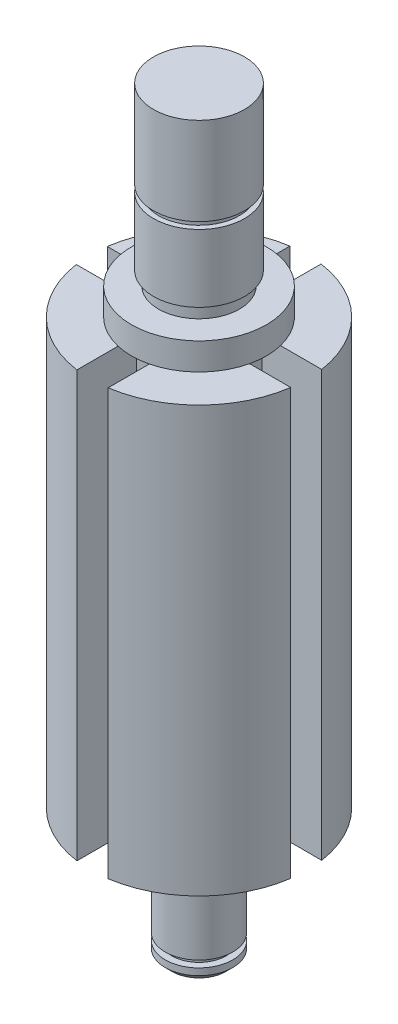
SolidWorks part; units mm, degrees
ref_plane "Plan de face" through (0, 0, 0) normal (0, 0, 1) x (1, 0, 0)
ref_plane "Plan de dessus" through (0, 0, 0) normal (0, 1, 0) x (1, 0, 0)
ref_plane "Plan de droite" through (0, 0, 0) normal (1, 0, 0) x (0, 0, -1)
sketch "Esquisse1" plane through (0, 0, 0) normal (0, 1, 0) x (1, 0, 0)
  line L0 (0, 0) -> (8, 0) construction
  line L1 (1.1802, -8) -> (1.1802, -3.5)
  line L2 (8, 1.1802) -> (3.5, 1.1802)
  line L3 (8, 1.1802) -> (8, -1.1244)
  line L4 (8, -1.1244) -> (3.5, -1.1244)
  line L5 (3.5, 1.1802) -> (3.5, -1.1244)
  line L6 (1.1802, -3.5) -> (-1.1244, -3.5)
  line L7 (-1.1244, -8) -> (-1.1244, -3.5)
  line L8 (1.1802, -8) -> (-1.1244, -8)
  line L9 (-8, -1.1802) -> (-3.5, -1.1802)
  line L10 (-3.5, -1.1802) -> (-3.5, 1.1244)
  line L11 (-8, 1.1244) -> (-3.5, 1.1244)
  line L12 (-8, -1.1802) -> (-8, 1.1244)
  line L13 (-1.1802, 8) -> (-1.1802, 3.5)
  line L14 (-1.1802, 3.5) -> (1.1244, 3.5)
  line L15 (1.1244, 8) -> (1.1244, 3.5)
  line L16 (-1.1802, 8) -> (1.1244, 8)
  circle A0 centre (0, 0) radius 8
  point P23 (0, 0)
  dimension "D1" = 16
  dimension "D2" = 4.5
  dimension "D3" = 4
extrude "Boss.-Extru.1" add sketch "Esquisse1" along normal blind 31.5
sketch "Esquisse3" plane through (0, 0, 0) normal (0, -1, 0) x (1, 0, 0)
  circle A0 centre (0, 0) radius 3.5
  dimension "D1" = 7
extrude "Boss.-Extru.2" add sketch "Esquisse3" along normal blind 3
sketch "Esquisse5" plane through (0, -3, 0) normal (0, -1, 0) x (1, 0, 0)
  circle A0 centre (0, 0) radius 2
  dimension "D1" = 4
extrude "Boss.-Extru.3" add sketch "Esquisse5" along normal blind 0.5
sketch "Esquisse6" plane through (0, -3.5, 0) normal (0, -1, 0) x (1, 0, 0)
  circle A0 centre (0, 0) radius 2.5
extrude "Boss.-Extru.4" add sketch "Esquisse6" along normal blind 4.5
sketch "Esquisse8" plane through (0, -8, 0) normal (0, -1, 0) x (1, 0, 0)
  circle A0 centre (0, 0) radius 2
  dimension "D1" = 4
extrude "Boss.-Extru.5" add sketch "Esquisse8" along normal blind 0.5
sketch "Esquisse9" plane through (0, -8.5, 0) normal (0, -1, 0) x (1, 0, 0)
  circle A0 centre (0, 0) radius 2.5
  dimension "D1" = 5
extrude "Boss.-Extru.6" add sketch "Esquisse9" along normal blind 1
chamfer "Chanfrein1" distance 0.5 angle 45 1 edges at (0, -9.5, -2.5)
sketch "Esquisse10" plane through (0, 31.5, 0) normal (0, 1, 0) x (1, 0, 0)
  circle A0 centre (0, 0) radius 5
  dimension "D1" = 10
extrude "Boss.-Extru.7" add sketch "Esquisse10" along normal blind 2
sketch "Esquisse11" plane through (0, 33.5, 0) normal (0, 1, 0) x (1, 0, 0)
  circle A0 centre (0, 0) radius 3
  dimension "D1" = 6
extrude "Boss.-Extru.8" add sketch "Esquisse11" along normal blind 1
sketch "Esquisse13" plane through (0, 34.5, 0) normal (0, 1, 0) x (1, 0, 0)
  circle A0 centre (0, 0) radius 3.375
  dimension "D1" = 6.75
extrude "Boss.-Extru.9" add sketch "Esquisse13" along normal blind 5
sketch "Esquisse15" plane through (0, 39.5, 0) normal (0, 1, 0) x (1, 0, 0)
  circle A0 centre (0, 0) radius 3
  dimension "D1" = 6
extrude "Boss.-Extru.10" add sketch "Esquisse15" along normal blind 0.5
sketch "Esquisse16" plane through (0, 40, 0) normal (0, 1, 0) x (1, 0, 0)
  circle A0 centre (0, 0) radius 3.375
  dimension "D1" = 6.75
extrude "Boss.-Extru.11" add sketch "Esquisse16" along normal blind 6.5
